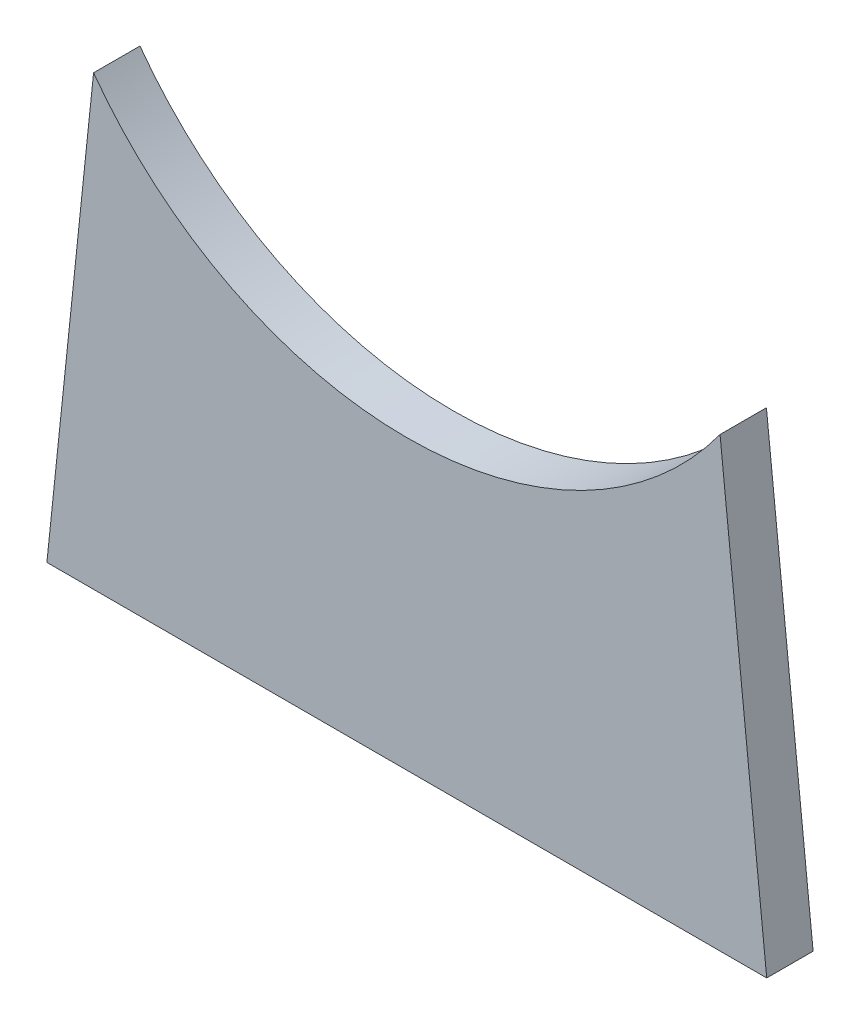
SolidWorks part; units mm, degrees
ref_plane "Front Plane" through (0, 0, 0) normal (0, 0, 1) x (1, 0, 0)
ref_plane "Top Plane" through (0, 0, 0) normal (0, 1, 0) x (1, 0, 0)
ref_plane "Right Plane" through (0, 0, 0) normal (1, 0, 0) x (0, 0, -1)
sketch "Sketch1" plane through (0, 0, 0) normal (0, 0, 1) x (1, 0, 0)
  line L0 (-1978.125, 0) -> (1978.125, 0)
  line L1 (0, 83.9107) -> (0, -90.8692) construction
  line L2 (1978.125, 0) -> (1721.625, 0) construction
  line L3 (1978.125, 0) -> (1721.625, 2458.75)
  line L5 (0, 1421.7215) -> (0, -1668.9716) construction
  line L7 (-1978.125, 0) -> (-1721.625, 2458.75)
  line L9 (0, 5580.8143) -> (0, 1421.7215) construction
  arc A1 (-1721.625, 2458.75) -> (1721.625, 2458.75) centre (0, 3712.9459) ccw
  dimension "D1" = 3956.25
  dimension "D2" = 2458.75
extrude "Boss-Extrude1" add sketch "Sketch1" along normal mid plane 255
